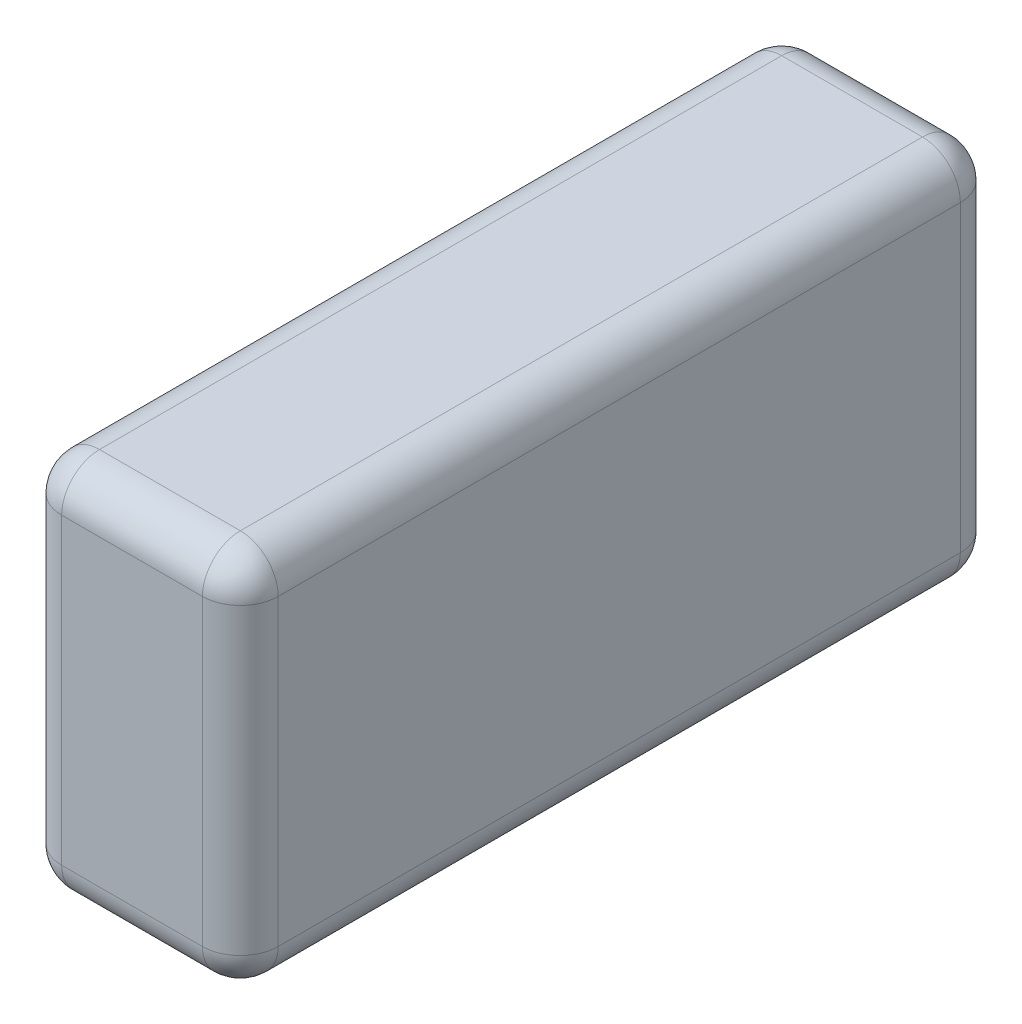
SolidWorks part; units mm, degrees
ref_plane "Front Plane" through (0, 0, 0) normal (0, 0, 1) x (1, 0, 0)
ref_plane "Top Plane" through (0, 0, 0) normal (0, 1, 0) x (1, 0, 0)
ref_plane "Right Plane" through (0, 0, 0) normal (1, 0, 0) x (0, 0, -1)
sketch "Sketch1" plane through (0, 0, 0) normal (1, 0, 0) x (0, 0, -1)
  line L1 (0, 0) -> (700, 0)
  line L2 (0, 0) -> (0, 350)
  line L3 (0, 350) -> (700, 350)
  line L4 (700, 0) -> (700, 350)
  dimension "D1" = 700
  dimension "D2" = 350
extrude "Boss-Extrude1" add sketch "Sketch1" against normal blind 200
fillet "Fillet1" radius 35 12 edges at (-100, 350, 0) (-100, 350, -700) (-100, 0, -700) (-100, 0, 0) (-200, 0, -350) (-200, 175, -700) (-200, 350, -350) (-200, 175, 0) (0, 350, -350) (0, 175, -700) (0, 0, -350) (0, 175, 0)
